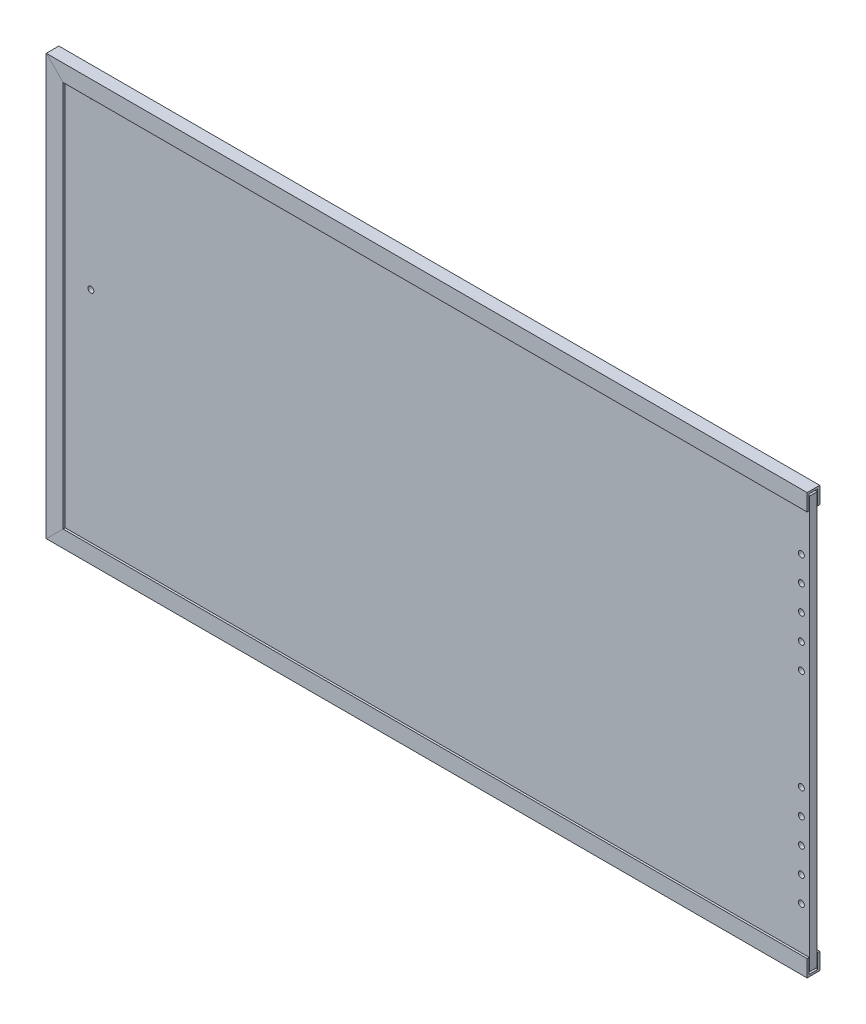
SolidWorks part; units mm, degrees
material "PC High Viscosity"
ref_plane "Front Plane" through (0, 0, 0) normal (0, 0, 1) x (1, 0, 0)
ref_plane "Top Plane" through (0, 0, 0) normal (0, 1, 0) x (1, 0, 0)
ref_plane "Right Plane" through (0, 0, 0) normal (1, 0, 0) x (0, 0, -1)
sketch "Shelf opening" plane through (0, 0, 0) normal (0, 0, 1) x (1, 0, 0)
  line L1 (0, 0) -> (577.85, 0)
  line L2 (0, 0) -> (0, 292.1)
  line L3 (0, 292.1) -> (577.85, 292.1)
  line L4 (577.85, 0) -> (577.85, 292.1)
  dimension "D1" = 577.85
  dimension "D2" = 292.1
sketch "Sketch2" plane through (0, 0, 0) normal (0, 0, 1) x (1, 0, 0)
  line L0 (577.85, 0) -> (577.85, 292.1) construction
  line L1 (3.175, 304.8) -> (577.85, 304.8)
  line L2 (3.175, 304.8) -> (3.175, -12.7)
  line L3 (3.175, -12.7) -> (577.85, -12.7)
  line L4 (577.85, 304.8) -> (577.85, -12.7)
  line L5 (0, 292.1) -> (577.85, 292.1) construction
  line L6 (0, 0) -> (0, 292.1) construction
  line L7 (0, 0) -> (577.85, 0) construction
  dimension "D1" = 12.7
  dimension "D2" = 3.175
  dimension "D3" = 12.7
extrude "Frame outer dimensions" add sketch "Sketch2" along normal mid plane 9.525
sketch "Sketch3" plane through (0, 0, 4.7625) normal (0, 0, 1) x (1, 0, 0)
  line L0 (577.85, -12.7) -> (577.85, 304.8) construction
  line L1 (577.85, 292.1) -> (15.875, 292.1)
  line L2 (577.85, 292.1) -> (577.85, 0)
  line L3 (577.85, 0) -> (15.875, 0)
  line L4 (15.875, 292.1) -> (15.875, 0)
  line L5 (577.85, 304.8) -> (3.175, 304.8) construction
  line L6 (3.175, 304.8) -> (3.175, -12.7) construction
  line L7 (3.175, -12.7) -> (577.85, -12.7) construction
  dimension "D1" = 12.7
  dimension "D2" = 12.7
  dimension "D3" = 12.7
extrude "Frame inner dimensions" cut sketch "Sketch3" against normal through all
sketch "Sketch4" plane through (0, 0, 0) normal (0, 0, 1) x (1, 0, 0)
  line L0 (577.85, 292.1) -> (577.85, 304.8) construction
  line L1 (577.85, 303.2125) -> (4.7625, 303.2125)
  line L2 (577.85, 303.2125) -> (577.85, -11.1125)
  line L3 (577.85, -11.1125) -> (4.7625, -11.1125)
  line L4 (4.7625, 303.2125) -> (4.7625, -11.1125)
  line L5 (577.85, 304.8) -> (3.175, 304.8) construction
  line L6 (3.175, 304.8) -> (3.175, -12.7) construction
  line L7 (3.175, -12.7) -> (577.85, -12.7) construction
  dimension "D1" = 1.5875
  dimension "D2" = 1.5875
  dimension "D3" = 1.5875
extrude "Frame profile" cut sketch "Sketch4" along normal offset from surface 1.5875 and the other way offset from surface (3.175 mm away) 1.5875 up to face at (293.6875, 146.05, 4.7625) other way up to face at (293.6875, 146.05, -4.7625)
sketch "Frame sections" plane through (0, 0, 4.7625) normal (0, 0, 1) x (1, 0, 0)
  line L0 (3.175, 304.8) -> (15.875, 292.1)
  line L1 (3.175, -12.7) -> (15.875, 0)
split "Frame section split" trim tools "Frame sections" bodies to split 103 resulting bodies 105 106 107
sketch "Sketch5" plane through (0, 0, 0) normal (0, 0, 1) x (1, 0, 0)
  line L0 (577.85, 292.1) -> (577.85, 304.8) construction
  line L1 (577.85, 301.625) -> (6.35, 301.625)
  line L2 (577.85, 301.625) -> (577.85, -9.525)
  line L3 (577.85, -9.525) -> (6.35, -9.525)
  line L4 (6.35, 301.625) -> (6.35, -9.525)
  line L5 (4.7625, 303.2125) -> (577.85, 303.2125) construction
  line L6 (4.7625, -11.1125) -> (4.7625, 303.2125) construction
  line L7 (577.85, -11.1125) -> (4.7625, -11.1125) construction
  dimension "D1" = 1.5875
  dimension "D2" = 1.5875
  dimension "D3" = 1.5875
  dimension "D4" = 571.5
  dimension "D5" = 311.15
extrude "Door panel" add sketch "Sketch5" along normal mid plane 5.588 separate body
sketch "Hinge positions" plane through (0, 0, 2.794) normal (0, 0, 1) x (1, 0, 0)
  line L0 (577.85, -9.525) -> (577.85, 301.625) construction
  line L1 (577.85, 269.875) -> (565.15, 269.875)
  line L2 (577.85, 269.875) -> (577.85, 174.625)
  line L3 (577.85, 174.625) -> (565.15, 174.625)
  line L4 (565.15, 269.875) -> (565.15, 174.625)
  line L5 (565.15, 117.475) -> (577.85, 117.475)
  line L6 (565.15, 117.475) -> (565.15, 22.225)
  line L7 (565.15, 22.225) -> (577.85, 22.225)
  line L8 (577.85, 117.475) -> (577.85, 22.225)
  line L10 (0, 0) -> (577.85, 0) construction
  line L11 (0, 292.1) -> (577.85, 292.1) construction
  dimension "D1" = 95.25
  dimension "D2" = 12.7
  dimension "D3" = 22.225
  dimension "D4" = 22.225
  dimension "D5" = 152.4
sketch "Sketch8" plane through (0, 0, 2.794) normal (0, 0, 1) x (1, 0, 0)
  line L0 (565.15, 69.85) -> (577.85, 69.85) construction
  line L2 (565.15, 117.475) -> (565.15, 22.225) construction
  line L3 (577.85, 117.475) -> (577.85, 22.225) construction
  line L4 (565.15, 222.25) -> (577.85, 222.25) construction
  line L6 (565.15, 269.875) -> (565.15, 174.625) construction
  line L7 (577.85, 269.875) -> (577.85, 174.625) construction
  point P0 (571.5, 31.75)
  point P11 (571.5, 50.8)
  point P12 (571.5, 69.85)
  point P13 (571.5, 88.9)
  point P14 (571.5, 107.95)
  point P15 (571.5, 203.2)
  point P16 (571.5, 222.25)
  point P17 (571.5, 241.3)
  point P18 (571.5, 260.35)
  point P19 (571.5, 184.15)
  dimension "D3" = 19.05
  dimension "D1" = 5
  dimension "D2" = 2
hole_wizard "#8 Clearance Hole1" positions "Sketch8" profile "Sketch9" hole size "#8" standard "ANSI Inch" end condition through all
sketch "Sketch9" plane through (571.5, 31.75, 2.794) normal (1, 0, 0) x (0, -1, 0)
  line L0 (0, 0) -> (0, 7.5565)
  line L1 (0, 7.5565) -> (2.2479, 7.5565)
  line L2 (2.2479, 7.5565) -> (2.2479, 0)
  line L5 (2.2479, 0) -> (0, 0)
  line L11 (0, -6.35) -> (0, 107.95) construction
  dimension "Thru Hole Dia." = 4.4958
  dimension "Thru Hole Depth" = 7.5565
sketch "Handle positions" plane through (0, 0, 2.794) normal (0, 0, 1) x (1, 0, 0)
  line L1 (6.35, 301.625) -> (44.45, 301.625)
  line L2 (6.35, 301.625) -> (6.35, 152.4)
  line L3 (6.35, 152.4) -> (44.45, 152.4)
  line L4 (44.45, 301.625) -> (44.45, 152.4)
  line L5 (6.35, 301.625) -> (6.35, -9.525) construction
  line L6 (577.85, 301.625) -> (6.35, 301.625) construction
  dimension "D1" = 149.225
  dimension "D2" = 38.1
sketch "Sketch11" plane through (0, 0, 2.794) normal (0, 0, 1) x (1, 0, 0)
  line L0 (34.925, 165.1) -> (34.925, 292.1) construction
  line L2 (6.35, 301.625) -> (6.35, 152.4) construction
  line L3 (6.35, 301.625) -> (44.45, 301.625) construction
  point P0 (34.925, 292.1)
  point P2 (34.925, 165.1)
  dimension "D1" = 28.575
  dimension "D2" = 9.525
  dimension "D3" = 136.525
hole_wizard "#8 Clearance Hole2" positions "Sketch11" profile "Sketch12" hole size "#8" standard "ANSI Inch" end condition through all
sketch "Sketch12" plane through (34.925, 292.1, 2.794) normal (1, 0, 0) x (0, -1, 0)
  line L0 (0, 0) -> (0, 7.5565)
  line L1 (0, 7.5565) -> (2.2479, 7.5565)
  line L2 (2.2479, 7.5565) -> (2.2479, 0)
  line L5 (2.2479, 0) -> (0, 0)
  line L11 (0, -6.35) -> (0, 107.95) construction
  dimension "Thru Hole Dia." = 4.4958
  dimension "Thru Hole Depth" = 7.5565
mirror "Mirror1" about plane through (0, 0, 0) normal (1, 0, 0) of bodies 105 106 107 114 108
delete or keep bodies "Body-Delete/Keep 1" type keep bodies bodies 105 106 107 114
delete or keep bodies "Body-Delete/Keep 2" [suppressed] type keep bodies bodies 109 110 111 112
